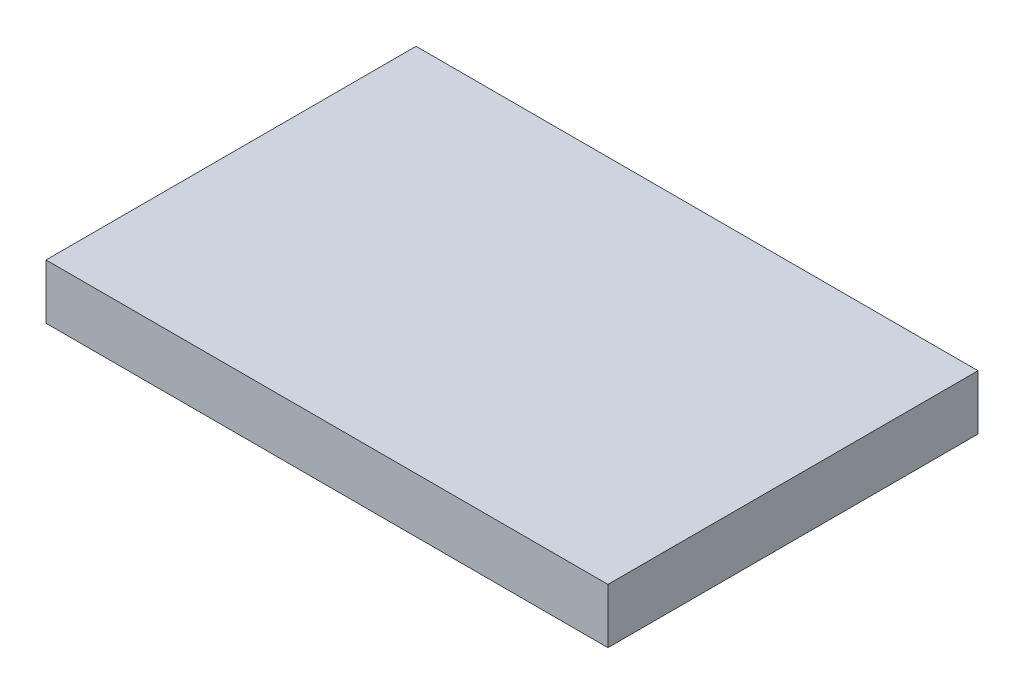
SolidWorks part; units mm, degrees
ref_plane "Front Plane" through (0, 0, 0) normal (0, 0, 1) x (1, 0, 0)
ref_plane "Top Plane" through (0, 0, 0) normal (0, 1, 0) x (1, 0, 0)
ref_plane "Right Plane" through (0, 0, 0) normal (1, 0, 0) x (0, 0, -1)
sketch "Sketch1" plane through (0, 0, 0) normal (0, 1, 0) x (1, 0, 0)
  line L1 (-41, -27) -> (41, -27)
  line L2 (-41, -27) -> (-41, 27)
  line L3 (-41, 27) -> (41, 27)
  line L4 (41, -27) -> (41, 27)
  line L5 (-41, -27) -> (41, 27) construction
  line L6 (-41, 27) -> (41, -27) construction
  point P0 (0, 0)
  dimension "D1" = 82
  dimension "D2" = 54
extrude "Boss-Extrude1" add sketch "Sketch1" along normal blind 8
